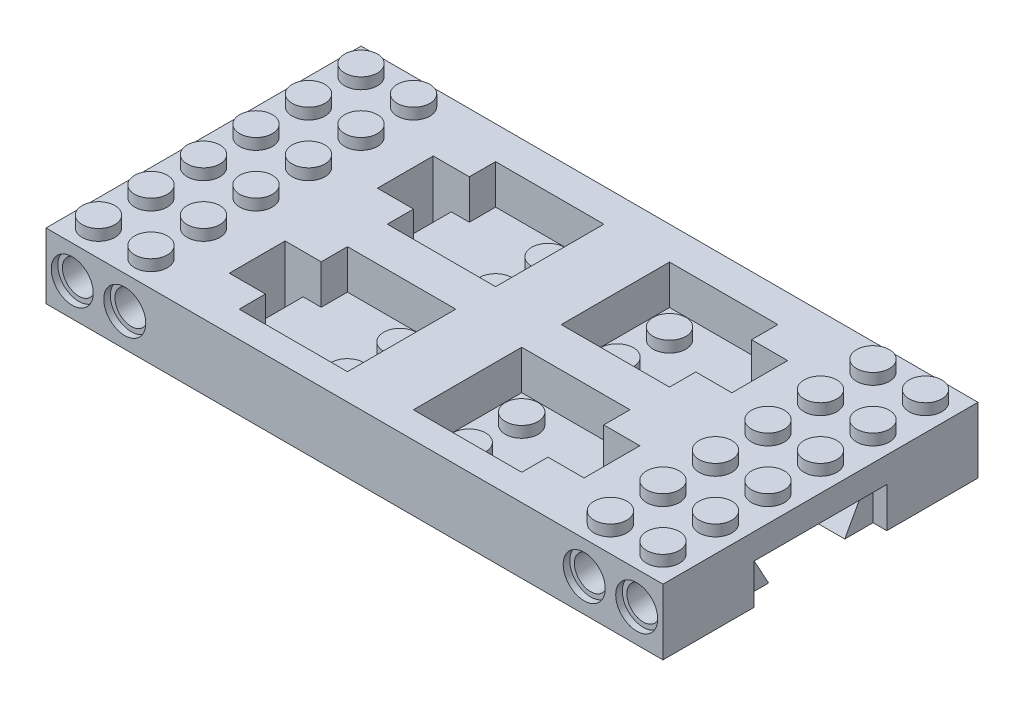
SolidWorks part; units mm, degrees
ref_plane "Front Plane" through (0, 0, 0) normal (0, 0, 1) x (1, 0, 0)
ref_plane "Top Plane" through (0, 0, 0) normal (0, 1, 0) x (1, 0, 0)
ref_plane "Right Plane" through (0, 0, 0) normal (1, 0, 0) x (0, 0, -1)
sketch "Sketch1" plane through (0, 0, 0) normal (0, 1, 0) x (1, 0, 0)
  line L0 (-47, 24) -> (47, -24) construction
  line L1 (-47, 24) -> (47, 24)
  line L2 (-47, 24) -> (-47, -24)
  line L3 (-47, -24) -> (47, -24)
  line L4 (47, 24) -> (47, -24)
  line L5 (-47, -24) -> (47, 24) construction
  point P4 (-47, 0)
  point P6 (0, -24)
  point P7 (0, 0)
  dimension "D1" = 48
  dimension "D2" = 94
extrude "Boss-Extrude1" add sketch "Sketch1" along normal blind 10
sketch "Sketch2" plane through (0, 10, 0) normal (0, 1, 0) x (1, 0, 0)
  line L8 (-21.5686, -3.5) -> (-5.0686, -3.5)
  line L9 (-5.0686, -3.5) -> (-5.0686, -20)
  line L10 (-5.0686, -20) -> (-21.5686, -20)
  line L11 (-21.5686, -20) -> (-21.5686, -16)
  line L12 (-21.5686, -16) -> (-27.0686, -16)
  line L13 (-27.0686, -16) -> (-27.0686, -7.5)
  line L14 (-27.0686, -7.5) -> (-21.5686, -7.5)
  line L15 (-21.5686, -7.5) -> (-21.5686, -3.5)
  line L16 (-21.5, 19) -> (-5, 19)
  line L17 (-5, 19) -> (-5, 2.5)
  line L18 (-5, 2.5) -> (-21.5, 2.5)
  line L19 (-21.5, 2.5) -> (-21.5, 6.5)
  line L20 (-21.5, 6.5) -> (-27, 6.5)
  line L21 (-27, 6.5) -> (-27, 15)
  line L22 (-27, 15) -> (-21.5, 15)
  line L23 (-21.5, 15) -> (-21.5, 19)
  line L24 (47, 24) -> (-47, 24) construction
  line L25 (5, 19) -> (5, 2.5)
  line L26 (5, 2.5) -> (21.5, 2.5)
  line L27 (21.5, 2.5) -> (21.5, 6.5)
  line L28 (21.5, 6.5) -> (27, 6.5)
  line L29 (27, 6.5) -> (27, 15)
  line L30 (27, 15) -> (21.5, 15)
  line L31 (21.5, 15) -> (21.5, 19)
  line L32 (21.5, 19) -> (5, 19)
  line L33 (4.9769, -3.5) -> (4.9769, -20)
  line L34 (4.9769, -20) -> (21.4769, -20)
  line L35 (21.4769, -20) -> (21.4769, -16)
  line L36 (21.4769, -16) -> (26.9769, -16)
  line L37 (26.9769, -16) -> (26.9769, -7.5)
  line L38 (26.9769, -7.5) -> (21.4769, -7.5)
  line L39 (21.4769, -7.5) -> (21.4769, -3.5)
  line L40 (21.4769, -3.5) -> (4.9769, -3.5)
  line L41 (47, -24) -> (47, 24) construction
  dimension "D1" = 16.5
  dimension "D2" = 16.5
  dimension "D3" = 22
  dimension "8.50" = 8.5
  dimension "D4" = 16.5
  dimension "D5" = 4
  dimension "D6" = 16.5
  dimension "D7" = 16.5
  dimension "D8" = 8.5
  dimension "D9" = 22
  dimension "D10" = 16.5
  dimension "D11" = 4
  dimension "D12" = 6
  dimension "D13" = 5
  dimension "D14" = 16.5
  dimension "D15" = 16.5
  dimension "D16" = 8.5
  dimension "D17" = 5.5
  dimension "D18" = 5.5
  dimension "D19" = 4
  dimension "D20" = 16.5
  dimension "D21" = 16.5
  dimension "D22" = 8.5
  dimension "D23" = 5.5
  dimension "D24" = 5.5
  dimension "D25" = 4
  dimension "D26" = 6
  dimension "D27" = 5
  dimension "D28" = 10
  dimension "D29" = 20
extrude "Cut-Extrude1" cut sketch "Sketch2" against normal blind 6
sketch "Sketch3" plane through (0, 10, 0) normal (0, 1, 0) x (1, 0, 0)
  line L0 (21.5, 6.5) -> (27, 6.5) construction
  line L1 (27, 15) -> (24.25, 15)
  line L2 (27, 15) -> (27, 6.5)
  line L3 (27, 6.5) -> (24.25, 6.5)
  line L4 (24.25, 15) -> (24.25, 6.5)
  line L5 (21.4769, -16) -> (26.9769, -16) construction
  line L6 (26.9769, -7.5) -> (24.2269, -7.5)
  line L7 (26.9769, -7.5) -> (26.9769, -16)
  line L8 (26.9769, -16) -> (24.2269, -16)
  line L9 (24.2269, -7.5) -> (24.2269, -16)
  line L10 (-27, 6.5) -> (-21.5, 6.5) construction
  line L11 (-27, 15) -> (-24.25, 15)
  line L12 (-27, 15) -> (-27, 6.5)
  line L13 (-27, 6.5) -> (-24.25, 6.5)
  line L14 (-24.25, 15) -> (-24.25, 6.5)
  line L15 (-27.0686, -16) -> (-21.5686, -16) construction
  line L16 (-27.0686, -7.5) -> (-24.3186, -7.5)
  line L17 (-27.0686, -7.5) -> (-27.0686, -16)
  line L18 (-27.0686, -16) -> (-24.3186, -16)
  line L19 (-24.3186, -7.5) -> (-24.3186, -16)
extrude "Cut-Extrude2" cut sketch "Sketch3" against normal blind 10
sketch "Sketch4" plane through (0, 4, 0) normal (0, 1, 0) x (1, 0, 0)
  line L0 (4.9769, -3.5) -> (4.9769, -20) construction
  line L1 (21.4769, -3.5) -> (4.9769, -3.5) construction
  line L2 (-5.0686, -3.5) -> (-21.5686, -3.5) construction
  line L3 (-5.0686, -20) -> (-5.0686, -3.5) construction
  line L5 (-5, 19) -> (-21.5, 19) construction
  line L6 (-5, 2.5) -> (-5, 19) construction
  line L8 (4.9769, -3.5) -> (4.9769, -20) construction
  line L9 (5, 2.5) -> (21.5, 2.5) construction
  line L10 (5, 19) -> (5, 2.5) construction
  circle A0 centre (9.2269, -7.75) radius 2.5
  circle A1 centre (9.2269, -15.75) radius 2.5
  circle A2 centre (-9.3186, -7.75) radius 2.5
  circle A3 centre (-9.3186, -15.75) radius 2.5
  circle A4 centre (-9.25, 14.75) radius 2.5
  circle A5 centre (-9.25, 6.75) radius 2.5
  circle A6 centre (9.25, 14.75) radius 2.5
  circle A7 centre (9.25, 6.75) radius 2.5
  dimension "D1" = 5
  dimension "D2" = 5
  dimension "D6" = 5
  dimension "D7" = 5
  dimension "D9" = 5
  dimension "D10" = 5
  dimension "D12" = 5
  dimension "D13" = 5
  dimension "D3" = 4.25
  dimension "D4" = 4.25
  dimension "D5" = 8
  dimension "D8" = 8
  dimension "D11" = 8
  dimension "D14" = 8
  dimension "D15" = 4.25
  dimension "D16" = 4.25
  dimension "D17" = 4.25
  dimension "D18" = 4.25
  dimension "D19" = 4.25
  dimension "D20" = 4.25
  dimension "D21" = 4.25
  dimension "D22" = 4.25
  dimension "D23" = 4.25
  dimension "D24" = 4.25
extrude "Boss-Extrude2" add sketch "Sketch4" along normal blind 1.7
sketch "Sketch5" plane through (0, 10, 0) normal (0, 1, 0) x (1, 0, 0)
  line L0 (-47, 24) -> (-47, -24) construction
  line L1 (47, 24) -> (-47, 24) construction
  line L2 (-47, -24) -> (47, -24) construction
  line L3 (0, -24) -> (0, 24) construction
  circle A0 centre (-43, 20) radius 2.5
  circle A1 centre (-43, 12) radius 2.5
  circle A2 centre (-35, 20) radius 2.5
  circle A3 centre (-35, 12) radius 2.5
  circle A4 centre (-35, 4) radius 2.5
  circle A5 centre (-35, -4) radius 2.5
  circle A6 centre (-35, -12) radius 2.5
  circle A7 centre (-35, -20) radius 2.5
  circle A8 centre (-43, 4) radius 2.5
  circle A9 centre (-43, -4) radius 2.5
  circle A10 centre (-43, -12) radius 2.5
  circle A11 centre (-43, -20) radius 2.5
  circle A12 centre (43, -20) radius 2.5
  circle A13 centre (43, -12) radius 2.5
  circle A14 centre (43, -4) radius 2.5
  circle A15 centre (43, 4) radius 2.5
  circle A16 centre (35, -20) radius 2.5
  circle A17 centre (35, -12) radius 2.5
  circle A18 centre (35, -4) radius 2.5
  circle A19 centre (35, 4) radius 2.5
  circle A20 centre (35, 12) radius 2.5
  circle A21 centre (35, 20) radius 2.5
  circle A22 centre (43, 12) radius 2.5
  circle A23 centre (43, 20) radius 2.5
  dimension "D1" = 5
  dimension "D5" = 5
  dimension "D2" = 4
  dimension "D3" = 8
  dimension "4" = 4
  dimension "D4" = 4
  dimension "D7" = 4
  dimension "D9" = 8
  dimension "D10" = 4
  dimension "D8" = 2
  dimension "D6" = 3
extrude "Boss-Extrude3" add sketch "Sketch5" along normal blind 1.7
sketch "Sketch6" plane through (0, 0, 24) normal (0, 0, 1) x (1, 0, 0)
  line L0 (0, 0) -> (0, 10) construction
  line L1 (-47, 10) -> (47, 10) construction
  line L2 (-47, 0) -> (47, 0) construction
  line L3 (-47, 10) -> (-47, 0) construction
  circle A0 centre (-43, 5) radius 2.5
  circle A1 centre (-35, 5) radius 2.5
  circle A2 centre (35, 5) radius 2.5
  circle A3 centre (43, 5) radius 2.5
  dimension "D1" = 5
  dimension "D2" = 5
  dimension "D3" = 5
  dimension "D4" = 4
  dimension "D5" = 8
extrude "Cut-Extrude3" cut sketch "Sketch6" against normal blind 10
sketch "Sketch11" plane through (0, 0, 24) normal (0, 0, 1) x (1, 0, 0)
  line L0 (0, 10) -> (0, 0) construction
  line L1 (-47, 10) -> (47, 10) construction
  line L2 (-47, 0) -> (47, 0) construction
  circle A0 centre (-43, 5) radius 3.2
  circle A1 centre (-35, 5) radius 3.2
  circle A2 centre (35, 5) radius 3.2
  circle A3 centre (43, 5) radius 3.2
  dimension "D1" = 6.4
extrude "Cut-Extrude4" cut sketch "Sketch11" against normal blind 1
sketch "Sketch12" plane through (0, 0, -24) normal (0, 0, -1) x (-1, 0, 0)
  line L0 (0, 10) -> (0, 0) construction
  line L1 (-47, 10) -> (47, 10) construction
  line L2 (-47, 0) -> (47, 0) construction
  line L3 (-47, 10) -> (-47, 0) construction
  circle A0 centre (-43, 5) radius 2.5
  circle A1 centre (-35, 5) radius 2.5
  circle A2 centre (35, 5) radius 2.5
  circle A3 centre (43, 5) radius 2.5
  dimension "D1" = 5
  dimension "D2" = 5
  dimension "D3" = 4
  dimension "D4" = 8
extrude "Cut-Extrude5" cut sketch "Sketch12" against normal blind 10
sketch "Sketch13" plane through (0, 0, -24) normal (0, 0, -1) x (-1, 0, 0)
  line L0 (0, 10) -> (0, 0) construction
  line L1 (-47, 10) -> (47, 10) construction
  circle A0 centre (-43, 5) radius 3.2
  circle A1 centre (-35, 5) radius 3.2
  circle A2 centre (35, 5) radius 3.2
  circle A3 centre (43, 5) radius 3.2
  dimension "D1" = 6.4
extrude "Cut-Extrude6" cut sketch "Sketch13" against normal blind 1
sketch "Sketch15" plane through (47, 0, 0) normal (1, 0, 0) x (0, 0, -1)
  line L0 (-24, 0) -> (24, 0) construction
  line L1 (-10.1, 6.1) -> (10.1, 6.1)
  line L2 (-10.1, 6.1) -> (-10.1, 0)
  line L3 (-10.1, 0) -> (10.1, 0)
  line L4 (10.1, 6.1) -> (10.1, 0)
  line L5 (-24, 10) -> (-24, 0) construction
  dimension "D1" = 13.9
  dimension "D2" = 20.2
  dimension "D3" = 6.1
extrude "Cut-Extrude7" cut sketch "Sketch15" against normal blind 2.1
sketch "Sketch16" plane through (44.9, 0, 0) normal (1, 0, 0) x (0, 0, -1)
  line L0 (-5.8, 0) -> (-8.05, 4.1)
  line L1 (-10.1, 0) -> (10.1, 0) construction
  line L3 (0, 0) -> (0, 17.3833) construction
  line L6 (-8.05, 4.1) -> (8.05, 4.1)
  line L7 (-5.8, 0) -> (5.8, 0)
  line L8 (5.8, 0) -> (8.05, 4.1)
  point P9 (0, 4.1)
  dimension "D1" = 16.1
  dimension "D2" = 4.1
  dimension "D3" = 11.6
  dimension "D4" = 61.243
sketch "Sketch17" plane through (-47, 0, 0) normal (-1, 0, 0) x (0, 0, 1)
  line L0 (0, 10) -> (0, 0) construction
  line L1 (-24, 10) -> (24, 10) construction
  line L2 (-9.4998, 0) -> (-12, 4.1)
  line L3 (-24, 0) -> (24, 0) construction
  line L4 (-12, 4.1) -> (-0.9, 4.1)
  line L5 (-0.9, 4.1) -> (-3.3998, 0)
  line L6 (-24, 10) -> (-24, 0) construction
  line L7 (0.9, 4.1) -> (3.3998, 0)
  line L8 (12, 4.1) -> (0.9, 4.1)
  line L9 (9.4998, 0) -> (12, 4.1)
  line L10 (-9.4998, 0) -> (-3.3998, 0)
  line L11 (3.3998, 0) -> (9.4998, 0)
  dimension "D1" = 4.1
  dimension "D2" = 11.1
  dimension "D3" = 58.625
  dimension "D4" = 6.1
  dimension "D5" = 58.629
  dimension "D6" = 12
extrude "Cut-Extrude9" cut sketch "Sketch17" against normal blind 12
sketch "Sketch19" plane through (-35, 0, 0) normal (-1, 0, 0) x (0, 0, 1)
  line L0 (-0.9, 4.1) -> (-12, 4.1)
  line L1 (-12, 4.1) -> (-12, 0)
  line L2 (-24, 0) -> (-9.4998, 0) construction
  line L3 (-12, 0) -> (-0.9, 0)
  line L4 (-3.3998, 0) -> (3.3998, 0) construction
  line L5 (-0.9, 0) -> (-0.9, 4.1)
  line L6 (0, 0) -> (0, 25.1918) construction
  line L7 (0.9, 0) -> (0.9, 4.1)
  line L8 (12, 0) -> (0.9, 0)
  line L9 (12, 4.1) -> (12, 0)
  line L10 (0.9, 4.1) -> (12, 4.1)
extrude "Cut-Extrude10" cut sketch "Sketch19" along normal blind 7.9
extrude "Cut-Extrude11" cut sketch "Sketch16" against normal blind 4.1
